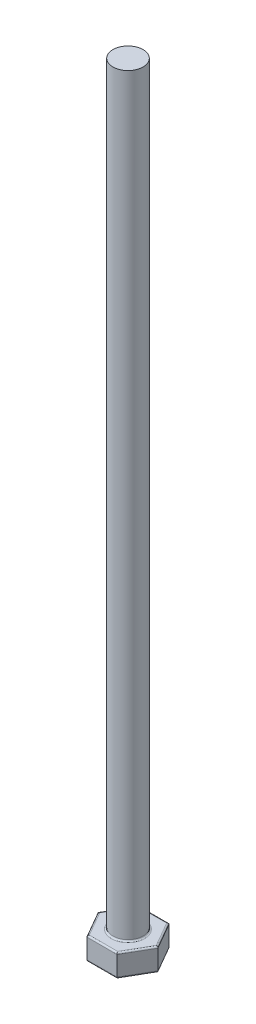
SolidWorks part; units mm, degrees
ref_plane "Front Plane" through (0, 0, 0) normal (0, 0, 1) x (1, 0, 0)
ref_plane "Top Plane" through (0, 0, 0) normal (0, 1, 0) x (1, 0, 0)
ref_plane "Right Plane" through (0, 0, 0) normal (1, 0, 0) x (0, 0, -1)
sketch "Sketch1" plane through (0, 0, 0) normal (0, 1, 0) x (1, 0, 0)
  circle A1 centre (0, 0) radius 2
  dimension "D1" = 4
extrude "Boss-Extrude1" add sketch "Sketch1" along normal blind 100
sketch "Sketch2" plane through (0, 0, 0) normal (0, -1, 0) x (1, 0, 0)
  line L1 (3.9837, 0) -> (1.9919, 3.45)
  line L2 (1.9919, 3.45) -> (-1.9919, 3.45)
  line L3 (-1.9919, 3.45) -> (-3.9837, 0)
  line L4 (-3.9837, 0) -> (-1.9919, -3.45)
  line L5 (-1.9919, -3.45) -> (1.9919, -3.45)
  line L6 (1.9919, -3.45) -> (3.9837, 0)
  circle A0 centre (0, 0) radius 3.45 construction
  point P1 (3.9837, 0)
  dimension "D1" = 6.9
extrude "Boss-Extrude2" add sketch "Sketch2" along normal blind 3
fillet "Fillet2" radius 0.2 13 edges at (0, -3, -3.45) (-2.9878, -3, -1.725) (-2.9878, -3, 1.725) (0, -3, 3.45) (2.9878, -3, 1.725) (2.9878, -3, -1.725) (2.9878, 0, 1.725) (0, 0, 3.45) (-2.9878, 0, 1.725) (-2.9878, 0, -1.725) (0, 0, -3.45) (2.9878, 0, -1.725) (0, 0, 2)
